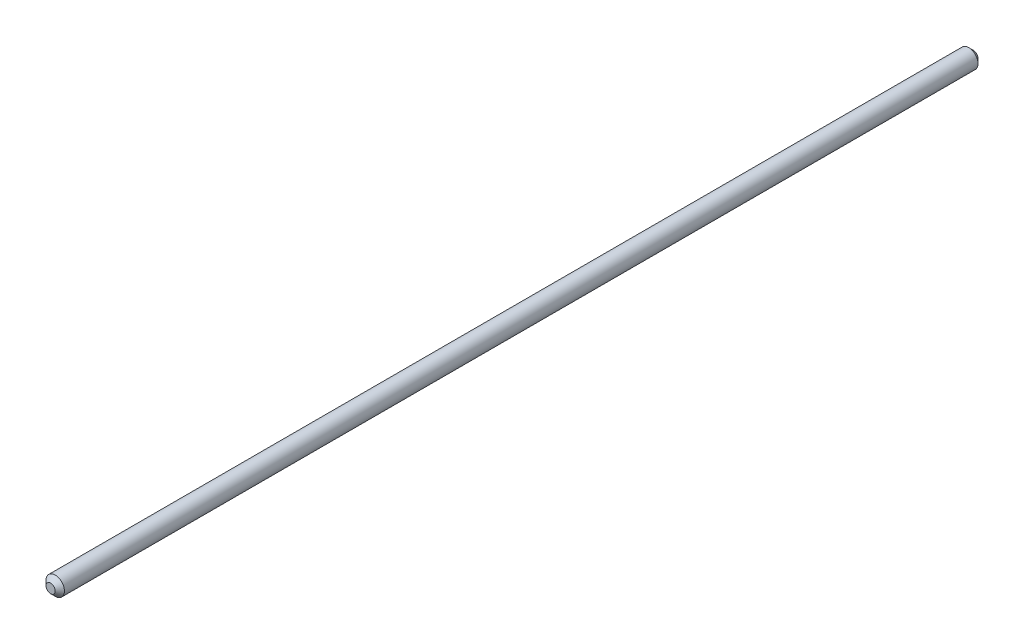
SolidWorks part; units mm, degrees
ref_plane "Alzado" through (0, 0, 0) normal (0, 0, 1) x (1, 0, 0)
ref_plane "Planta" through (0, 0, 0) normal (0, 1, 0) x (1, 0, 0)
ref_plane "Vista lateral" through (0, 0, 0) normal (1, 0, 0) x (0, 0, -1)
sketch "Croquis1" plane through (0, 0, 0) normal (0, 0, 1) x (1, 0, 0)
  circle A0 centre (0, 0) radius 4
  dimension "D1" = 8
extrude "Saliente-Extruir1" add sketch "Croquis1" along normal blind 400
chamfer "Chaflán1" distance 2 angle 45 2 edges at (4, 0, 400) (4, 0, 0)
